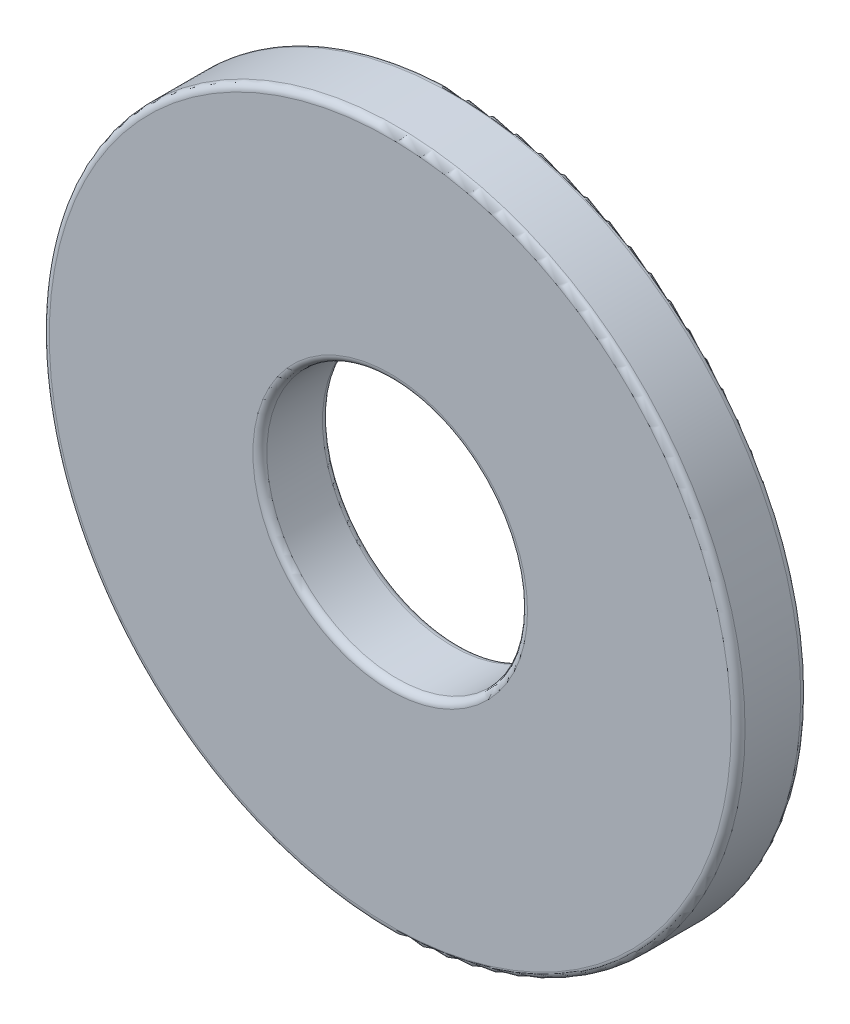
SolidWorks part; units mm, degrees
ref_plane "Front Plane" through (0, 0, 0) normal (0, 0, 1) x (1, 0, 0)
ref_plane "Top Plane" through (0, 0, 0) normal (0, 1, 0) x (1, 0, 0)
ref_plane "Right Plane" through (0, 0, 0) normal (1, 0, 0) x (0, 0, -1)
sketch "Sketch1" plane through (0, 0, 0) normal (0, 0, 1) x (1, 0, 0)
  circle A0 centre (0, 0) radius 3.5687
  circle A1 centre (0, 0) radius 9.525
  point P4 (0, 9.525)
  point P5 (0, 3.5687)
  point P6 (0, -3.5687)
  point P7 (3.5687, 0)
  point P8 (-3.5687, 0)
  dimension "OD" = 19.05
  dimension "ID" = 7.1374
sketch "Sketch2" plane through (0, 0, 0) normal (1, 0, 0) x (0, 0, -1)
  line L1 (-0.9525, 9.525) -> (0.9525, 9.525)
  line L2 (-0.9525, 9.525) -> (-0.9525, -9.525)
  line L3 (-0.9525, -9.525) -> (0.9525, -9.525)
  line L4 (0.9525, 9.525) -> (0.9525, -9.525)
  point P4 (0, 9.525)
  point P5 (0.9525, 0)
  dimension "Thickness" = 1.905
sketch "Sketch3" plane through (0, 0, 0) normal (0, 0, 1) x (1, 0, 0)
  circle A0 centre (0, 0) radius 3.5687 construction
  circle A1 centre (0, 0) radius 9.525 construction
  circle A2 centre (0, 0) radius 3.5687
  circle A3 centre (0, 0) radius 9.525
extrude "Boss-Extrude1" add sketch "Sketch3" against normal up to vertex (0.9525 mm away) from vertex at 0.9525 starting at point (0, 9.525, 0.9525)
fillet "Fillet1" radius 0.1905 4 edges at (3.5687, 0, 0.9525) (3.5687, 0, -0.9525) (9.525, 0, 0.9525) (9.525, 0, -0.9525)
equation "\"D1@Fillet1\"=\"Thickness@Sketch2\"*.1"
